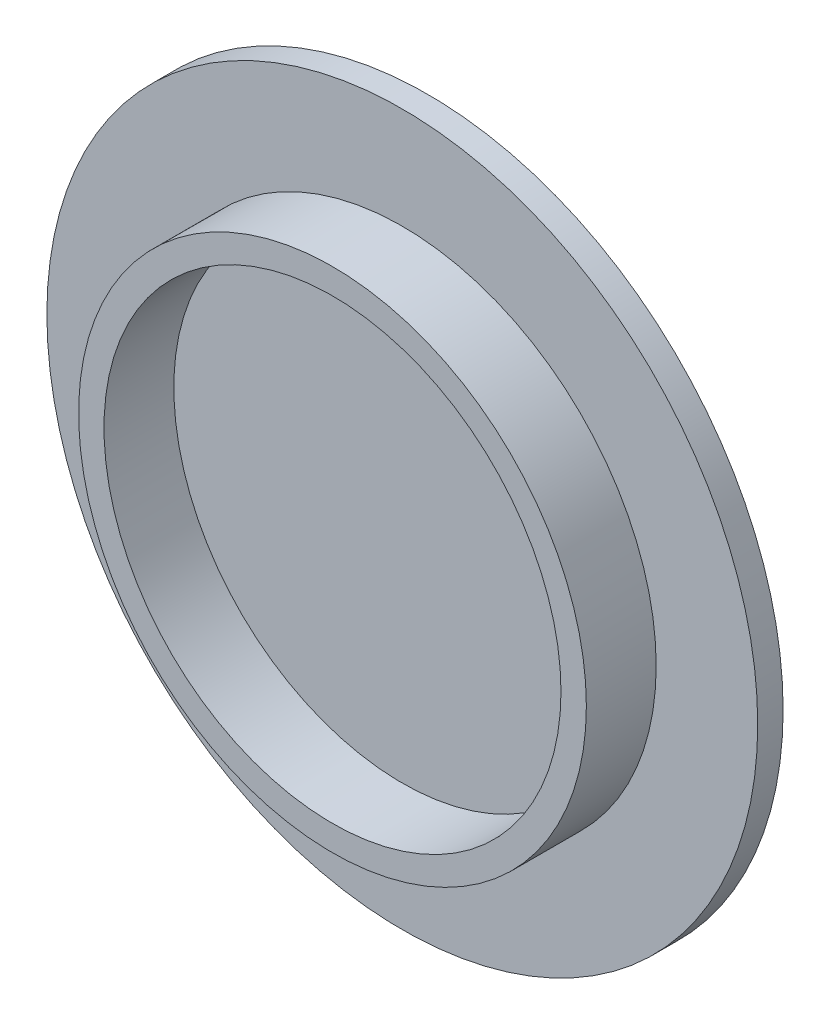
SolidWorks part; units mm, degrees
ref_plane "前视" through (0, 0, 0) normal (0, 0, 1) x (1, 0, 0)
ref_plane "上视" through (0, 0, 0) normal (0, 1, 0) x (1, 0, 0)
ref_plane "右视" through (0, 0, 0) normal (1, 0, 0) x (0, 0, -1)
sketch "草图1" plane through (0, 0, 0) normal (0, 0, 1) x (1, 0, 0)
  line L0 (0, 149.6675) -> (0, -153.1685) construction
  line L1 (-173.2992, 0) -> (179.7177, 0) construction
  circle A0 centre (0, 0) radius 140
  dimension "D1" = 280
extrude "拉伸1" add sketch "草图1" along normal blind 10
sketch "草图2" plane through (0, 0, 10) normal (0, 0, 1) x (1, 0, 0)
  circle A0 centre (0, 0) radius 100
  circle A1 centre (0, 0) radius 90
  dimension "D1" = 200
  dimension "D2" = 180
extrude "拉伸2" add sketch "草图2" along normal blind 27.5
